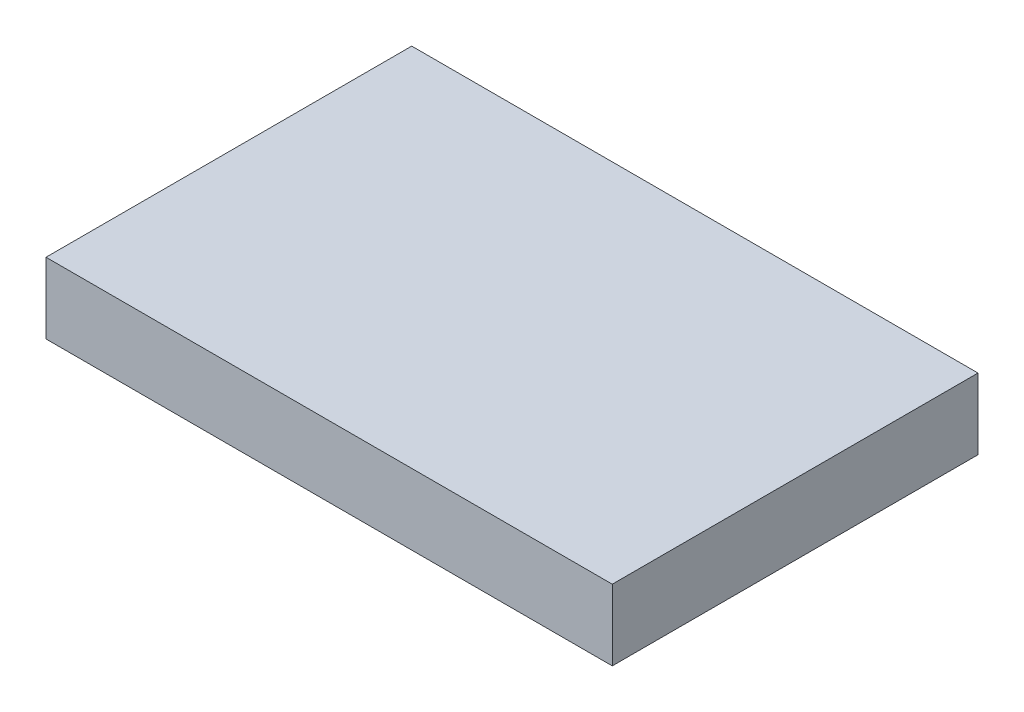
SolidWorks part; units mm, degrees
ref_plane "Front Plane" through (0, 0, 0) normal (0, 0, 1) x (1, 0, 0)
ref_plane "Top Plane" through (0, 0, 0) normal (0, 1, 0) x (1, 0, 0)
ref_plane "Right Plane" through (0, 0, 0) normal (1, 0, 0) x (0, 0, -1)
sketch "Sketch1" plane through (0, 0, 0) normal (0, 1, 0) x (1, 0, 0)
  line L1 (-24, -15.5) -> (24, -15.5)
  line L2 (-24, -15.5) -> (-24, 15.5)
  line L3 (-24, 15.5) -> (24, 15.5)
  line L4 (24, -15.5) -> (24, 15.5)
  line L5 (-24, -15.5) -> (24, 15.5) construction
  line L6 (-24, 15.5) -> (24, -15.5) construction
  point P0 (0, 0)
  dimension "D1" = 48
  dimension "D2" = 31
extrude "Boss-Extrude1" add sketch "Sketch1" along normal blind 6
